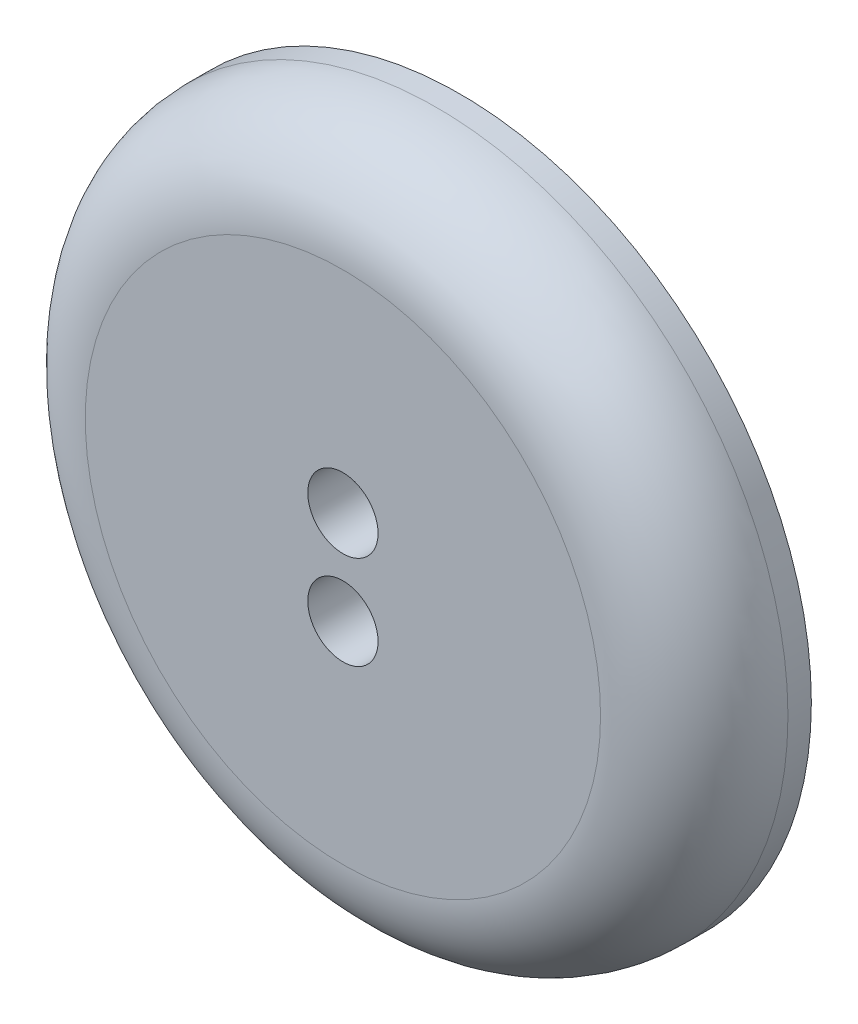
SolidWorks part; units mm, degrees
material "Custom Plastic"
ref_plane "Front Plane" through (0, 0, 0) normal (0, 0, 1) x (1, 0, 0)
ref_plane "Top Plane" through (0, 0, 0) normal (0, 1, 0) x (1, 0, 0)
ref_plane "Right Plane" through (0, 0, 0) normal (1, 0, 0) x (0, 0, -1)
sketch "Sketch1" plane through (0, 0, 0) normal (0, 0, 1) x (1, 0, 0)
  line L0 (0, -15) -> (0, 15)
  circle A0 centre (0, 0) radius 15
  circle A1 centre (0, 2) radius 1.5
  circle A2 centre (0, -2) radius 1.5
  dimension "D1" = 30
  dimension "D2" = 3
  dimension "D3" = 3
  dimension "D4" = 2
  dimension "D5" = 2
extrude "Boss-Extrude1" add sketch "Sketch1" along normal blind 5 contours A0 | A1 | A2
fillet "Fillet3" radius 4 1 edges at (15, 0, 5)
